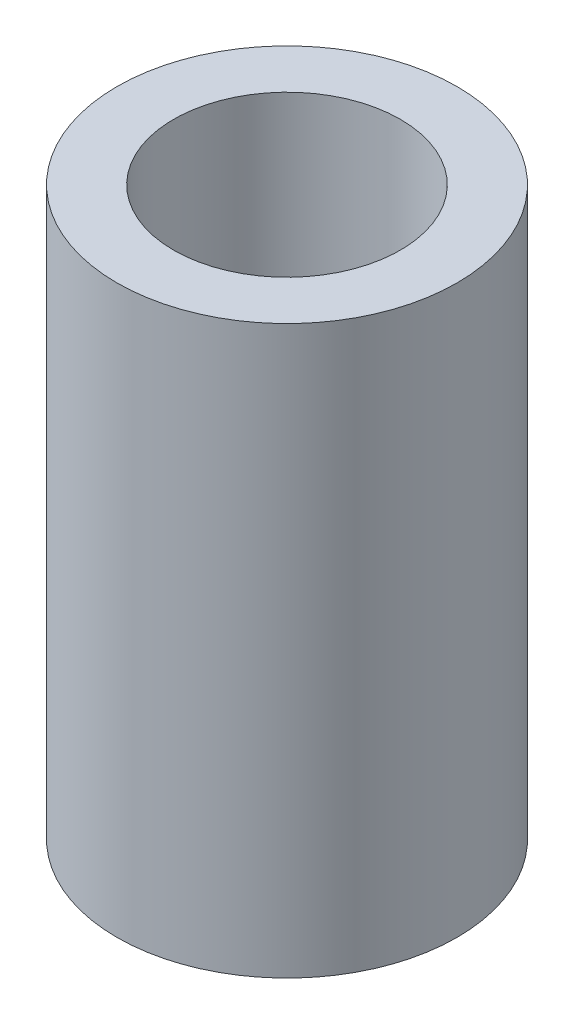
SolidWorks part; units mm, degrees
ref_plane "Front Plane" through (0, 0, 0) normal (0, 0, 1) x (1, 0, 0)
ref_plane "Top Plane" through (0, 0, 0) normal (0, 1, 0) x (1, 0, 0)
ref_plane "Right Plane" through (0, 0, 0) normal (1, 0, 0) x (0, 0, -1)
sketch "Sketch1" plane through (0, 0, 0) normal (0, 1, 0) x (1, 0, 0)
  circle A0 centre (0, 0) radius 3.175
  circle A1 centre (0, 0) radius 4.7625
  dimension "D1" = 6.35
  dimension "D2" = 9.525
extrude "Boss-Extrude1" add sketch "Sketch1" along normal blind 15.875
